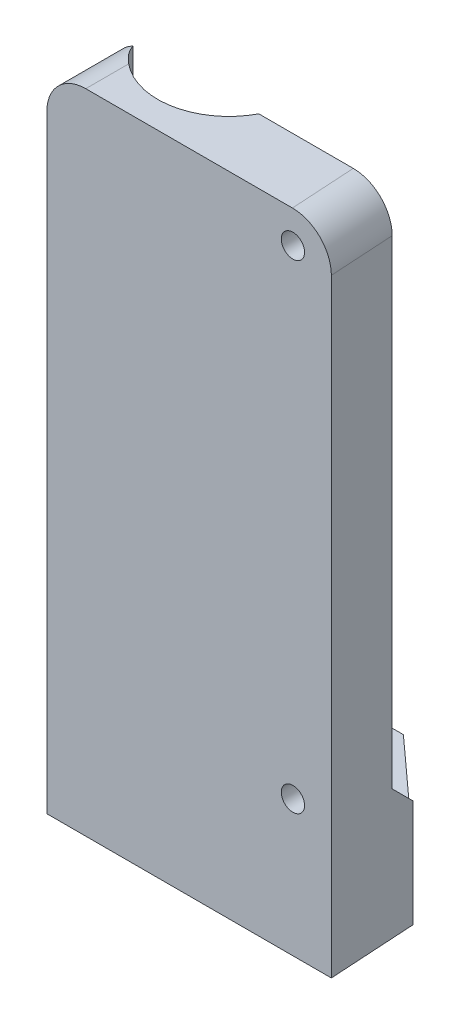
SolidWorks part; units mm, degrees
ref_plane "Front Plane" through (0, 0, 0) normal (0, 0, 1) x (1, 0, 0)
ref_plane "Top Plane" through (0, 0, 0) normal (0, 1, 0) x (1, 0, 0)
ref_plane "Right Plane" through (0, 0, 0) normal (1, 0, 0) x (0, 0, -1)
sketch "Sketch1" plane through (0, 0, 0) normal (0, 1, 0) x (1, 0, 0)
  line L0 (0, 0) -> (0, -3.25) construction
  line L1 (-5.3208, 8) -> (-22.469, -7.56)
  line L3 (-11.3345, 0) -> (11.3345, 0) construction
  line L4 (5.3208, 8) -> (22.469, -7.56)
  line L5 (-22.469, -7.56) -> (22.469, -7.56)
  line L6 (-5.3208, 8) -> (5.3208, 8)
  circle A0 centre (0, 0) radius 3.25
  dimension "D1" = 6.5
  dimension "D2" = 42.22
  dimension "D3" = 7.56
  dimension "D4" = 9.5
  dimension "D5" = 8
extrude "Boss-Extrude1" add sketch "Sketch1" along normal blind 50
chamfer "Chamfer4" distance 7 distance2 10 1 edges at (22.469, 25, 7.56)
sketch "Sketch2" plane through (0, 50, 0) normal (0, 1, 0) x (1, 0, 0)
  circle A0 centre (0, 0) radius 5.5
  dimension "D1" = 11
extrude "Cut-Extrude1" cut sketch "Sketch2" along direction (0, -1, 0) on the side against the normal offset from surface (45 mm away) 5
sketch "Sketch4" plane through (0, 0, 0) normal (0, -1, 0) x (1, 0, 0)
  line L0 (-6.5, 0) -> (-6.5, 8.4553)
  line L1 (0, -6.5) -> (12.1315, -6.5)
  line L2 (-6.5, 8.4553) -> (-18.0929, 18.5095)
  line L3 (-18.0929, 18.5095) -> (-27.844, 13.2665)
  line L4 (-27.844, 13.2665) -> (-26.2398, -3.9571)
  line L5 (-26.2398, -3.9571) -> (-22.0516, -11.7465)
  line L7 (12.1315, -6.5) -> (6.4453, -11.9042)
  line L8 (6.4453, -11.9042) -> (-22.0516, -11.7465)
  circle A1 centre (0, 0) radius 5.5 construction
  circle A2 centre (0, 0) radius 5.5 construction
  circle A3 centre (0, 0) radius 6.5 construction
  arc A4 (0, -6.5) -> (-6.5, 0) centre (0, 0) cw
  point P2 (-13.5601, 14.5783)
  point P16 (-27.844, 13.2665)
  point P17 (-26.2398, -3.9571)
  dimension "D1" = 1
extrude "Cut-Extrude3" cut sketch "Sketch4" against normal blind 50 and the other way through all
sketch "Sketch5" plane through (0, 50, 0) normal (0, 1, 0) x (1, 0, 0)
  line L0 (0, 0) -> (4.8679, -2.56)
  line L4 (-4.8679, -2.56) -> (0, 0)
  line L6 (-4.8679, -2.56) -> (-9.589, -2.56)
  line L7 (4.8679, -2.56) -> (20.4828, -2.56)
  line L8 (20.4828, -2.56) -> (8.2569, 8.38)
  line L9 (8.2569, 8.38) -> (1.3414, 8.38)
  line L10 (1.3414, 8.38) -> (-9.589, 8.38)
  line L11 (-9.589, 8.38) -> (-9.589, -2.56)
  line L13 (-6.5, -7.56) -> (15.469, -7.56) construction
  circle A0 centre (0, 0) radius 5.5 construction
  point P3 (5.5, 0)
  point P4 (5.3098, -1.4341)
  point P11 (18.8802, 0)
  point P12 (6.8138, 0)
  dimension "D1" = 5
extrude "Cut-Extrude4" cut sketch "Sketch5" against normal up to surface (45 mm away) up to face at (0, 5, -3.25)
chamfer "Chamfer5" distance 5 angle 45 2 edges at (10.0175, 5, 2.56) (-5.6839, 5, 2.56)
sketch "Sketch3" plane through (0, 0, 7.56) normal (0, 0, 1) x (1, 0, 0)
  line L0 (-6.5, 0) -> (15.469, 0) construction
  line L1 (12.5, 10.5) -> (-2.5, 10.5) construction
  line L2 (12.5, 10.5) -> (12.5, 47.5) construction
  line L3 (12.5, 47.5) -> (-2.5, 47.5) construction
  line L4 (-2.5, 10.5) -> (-2.5, 47.5) construction
  line L5 (12.5, 10.5) -> (-2.5, 47.5) construction
  line L6 (12.5, 47.5) -> (-2.5, 10.5) construction
  line L7 (0, -7.733) -> (0, 7.733) construction
  circle A0 centre (-2.5, 47.5) radius 0.9 construction
  circle A1 centre (12.5, 47.5) radius 0.9
  circle A2 centre (12.5, 10.5) radius 0.9
  circle A3 centre (-2.5, 10.5) radius 0.9 construction
  point P0 (5, 29)
  point P12 (0, 20)
  point P13 (3.0728, 20)
  point P16 (0, 0)
  dimension "D4" = 1.8
  dimension "D1" = 15
  dimension "D2" = 37
  dimension "D3" = 29
  dimension "D5" = 5
extrude "Cut-Extrude5" cut sketch "Sketch3" against normal blind 10
fillet "Fillet1" radius 3 2 edges at (15.3181, 50, 5.06) (-6.5, 50, 5.06)
